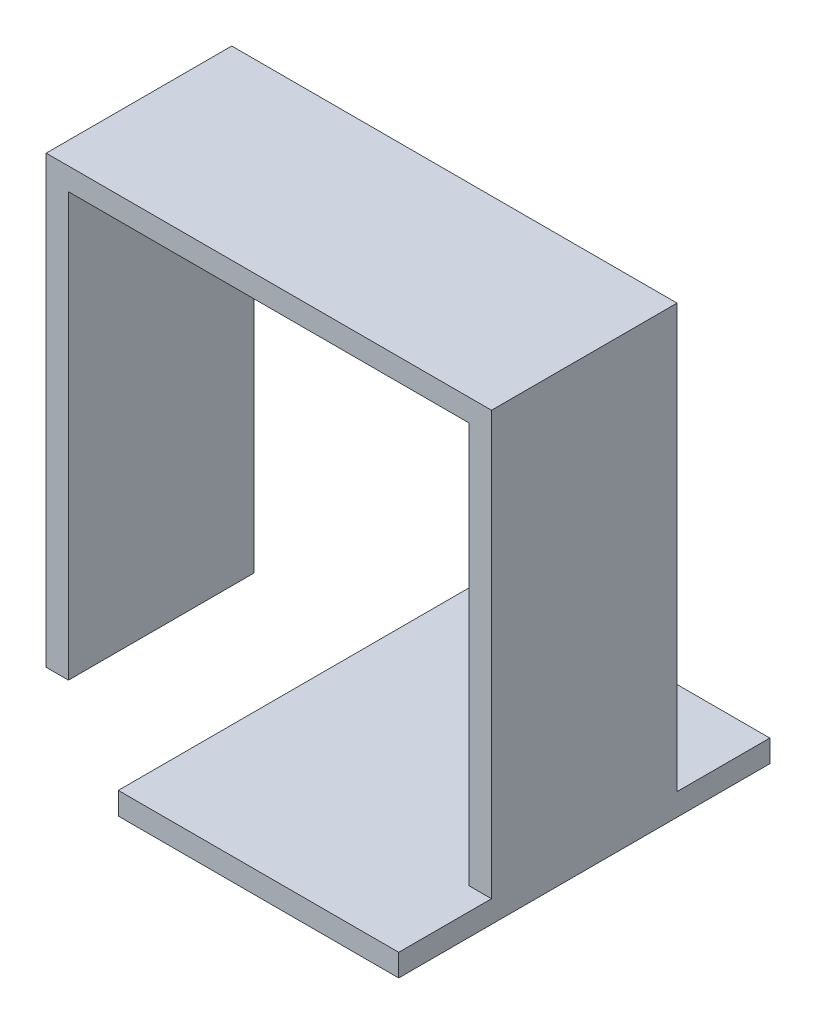
SolidWorks part; units mm, degrees
material "1060 Alloy"
ref_plane "Front Plane" through (0, 0, 0) normal (0, 0, 1) x (1, 0, 0)
ref_plane "Top Plane" through (0, 0, 0) normal (0, 1, 0) x (1, 0, 0)
ref_plane "Right Plane" through (0, 0, 0) normal (1, 0, 0) x (0, 0, -1)
sketch "Sketch1" plane through (0, 0, 0) normal (0, 1, 0) x (1, 0, 0)
  line L1 (-19.6273, -16.3945) -> (10.8527, -16.3945)
  line L2 (-19.6273, -16.3945) -> (-19.6273, 9.0055)
  line L3 (-19.6273, 9.0055) -> (10.8527, 9.0055)
  line L4 (10.8527, -16.3945) -> (10.8527, 9.0055)
  dimension "D1" = 30.48
  dimension "D2" = 25.4
extrude "Boss-Extrude1" add sketch "Sketch1" along normal blind 30.48
sketch "Sketch5" plane through (10.8527, 0, 0) normal (1, 0, 0) x (0, 0, -1)
  line L0 (-16.3945, 0) -> (9.0055, 0) construction
  line L1 (-16.3945, 30.48) -> (-10.0445, 30.48)
  line L2 (-16.3945, 30.48) -> (-16.3945, 1.524)
  line L3 (-16.3945, 1.524) -> (-10.0445, 1.524)
  line L4 (-10.0445, 30.48) -> (-10.0445, 1.524)
  line L5 (9.0055, 30.48) -> (2.6555, 30.48)
  line L6 (9.0055, 30.48) -> (9.0055, 1.524)
  line L7 (9.0055, 1.524) -> (2.6555, 1.524)
  line L8 (2.6555, 30.48) -> (2.6555, 1.524)
  dimension "D1" = 1.524
  dimension "D2" = 1.524
  dimension "D3" = 12.7
  dimension "D4" = 6.35
extrude "Cut-Extrude4" cut sketch "Sketch5" against normal through all
sketch "Sketch6" plane through (0, 0, 0) normal (0, 0, 1) x (1, 0, 0)
  line L0 (-18.1033, 0) -> (-18.1033, 28.956)
  line L2 (-18.1033, 28.956) -> (9.3287, 28.956)
  line L3 (9.3287, 28.956) -> (9.3287, 1.524)
  line L4 (9.3287, 1.524) -> (-8.3424, 1.524)
  line L5 (-8.3424, 1.524) -> (-8.3424, 0)
  line L6 (-8.3424, 0) -> (-18.1033, 0)
  line L10 (-19.6273, 0) -> (10.8527, 0) construction
  line L11 (-19.6273, 1.524) -> (-19.6273, 30.48) construction
  line L12 (-19.6273, 30.48) -> (10.8527, 30.48) construction
  line L13 (10.8527, 1.524) -> (10.8527, 30.48) construction
  dimension "D1" = 0
  dimension "D2" = 1.524
  dimension "D3" = 1.524
  dimension "D4" = 1.524
  dimension "D5" = 1.524
extrude "Cut-Extrude5" cut sketch "Sketch6" against normal through all both and the other way through all
sketch "Sketch7" plane through (-18.1033, 0, 0) normal (1, 0, 0) x (0, 0, -1)
  line L1 (-10.0445, 1.524) -> (-16.3945, 1.524)
  line L2 (-10.0445, 1.524) -> (-10.0445, 0)
  line L3 (-10.0445, 0) -> (-16.3945, 0)
  line L4 (-16.3945, 1.524) -> (-16.3945, 0)
  line L5 (2.6555, 1.524) -> (9.0055, 1.524)
  line L6 (2.6555, 1.524) -> (2.6555, 0)
  line L7 (2.6555, 0) -> (9.0055, 0)
  line L8 (9.0055, 1.524) -> (9.0055, 0)
extrude "Cut-Extrude6" cut sketch "Sketch7" against normal blind 31.75
